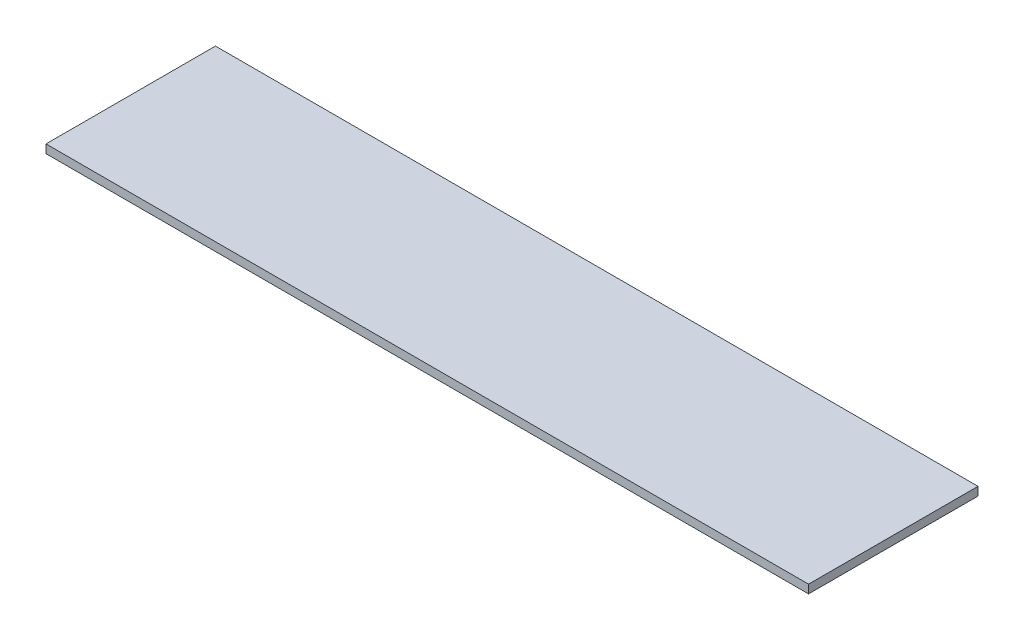
SolidWorks part; units mm, degrees
ref_plane "Plan de face" through (0, 0, 0) normal (0, 0, 1) x (1, 0, 0)
ref_plane "Plan de dessus" through (0, 0, 0) normal (0, 1, 0) x (1, 0, 0)
ref_plane "Plan de droite" through (0, 0, 0) normal (1, 0, 0) x (0, 0, -1)
sketch "Esquisse1" plane through (0, 0, 0) normal (0, 1, 0) x (1, 0, 0)
  line L1 (0, -100) -> (900, -100)
  line L2 (0, -100) -> (0, 100)
  line L3 (0, 100) -> (900, 100)
  line L4 (900, -100) -> (900, 100)
  dimension "D1" = 200
  dimension "D2" = 900
extrude "Boss.-Extru.1" add sketch "Esquisse1" along normal blind 10
